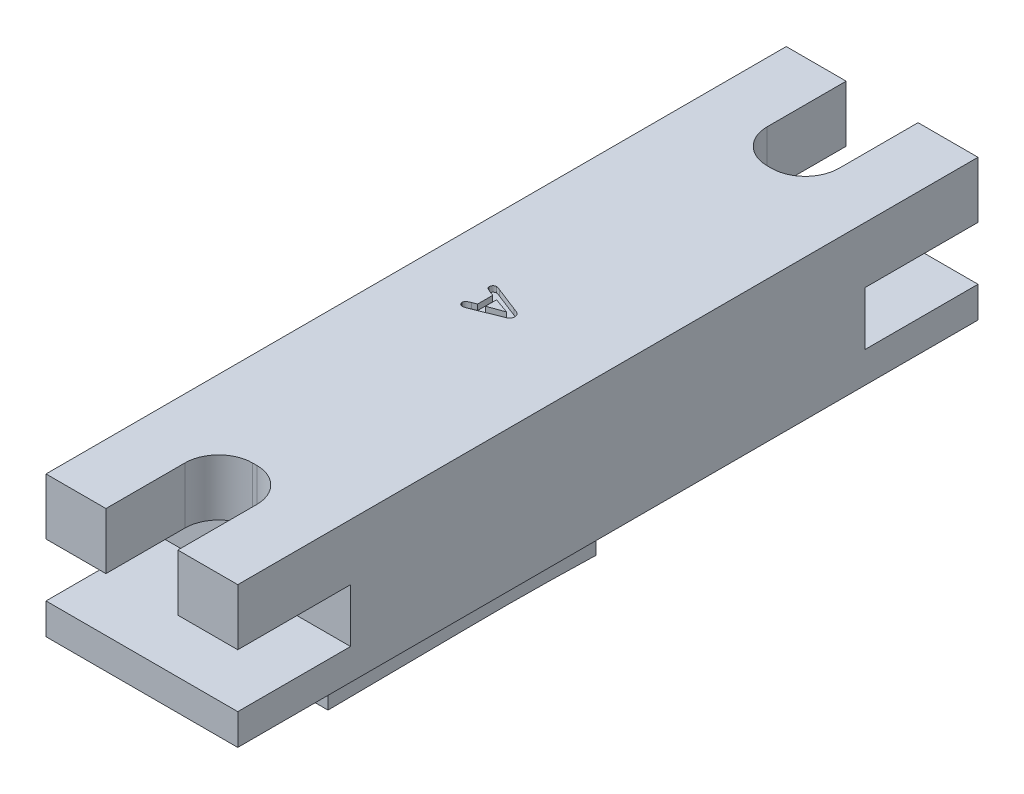
SolidWorks part; units mm, degrees
ref_plane "Front Plane" through (0, 0, 0) normal (0, 0, 1) x (1, 0, 0)
ref_plane "Top Plane" through (0, 0, 0) normal (0, 1, 0) x (1, 0, 0)
ref_plane "Right Plane" through (0, 0, 0) normal (1, 0, 0) x (0, 0, -1)
sketch "Sketch2" plane through (0, 0, 0) normal (0, 1, 0) x (1, 0, 0)
  line L1 (0, 0) -> (17.272, 0)
  line L2 (0, 0) -> (0, 66.675)
  line L3 (0, 66.675) -> (17.272, 66.675)
  line L4 (17.272, 0) -> (17.272, 66.675)
  dimension "D1" = 66.675
  dimension "D2" = 17.272
extrude "Boss-Extrude1" add sketch "Sketch2" along normal blind 12.7
sketch "Sketch3" plane through (0, 0, 0) normal (0, -1, 0) x (1, 0, 0)
  line L0 (17.272, -66.675) -> (0, -66.675) construction
  line L1 (2.54, 0) -> (7.62, 0)
  line L2 (2.54, 0) -> (2.54, -66.675)
  line L3 (2.54, -66.675) -> (7.62, -66.675)
  line L4 (7.62, 0) -> (7.62, -66.675)
  line L5 (0, -66.675) -> (0, 0) construction
  line L6 (0, 0) -> (17.272, 0) construction
  line L7 (-16.0623, -37.465) -> (21.3262, -37.465) construction
  line L8 (-9.1988, -29.21) -> (67.1361, -29.21) construction
  line L9 (2.54, -37.465) -> (2.54, -29.21) construction
  line L10 (-21.0326, -20.955) -> (28.4478, -20.955) construction
  line L11 (5.08, 0) -> (5.08, -66.675) construction
  line L12 (-27.1779, -45.72) -> (27.7068, -45.72) construction
  line L13 (2.54, -48.895) -> (2.54, -50.165)
  line L14 (7.62, -48.895) -> (2.54, -48.895) construction
  line L15 (7.62, -48.895) -> (7.62, -42.545) construction
  line L16 (7.62, -42.545) -> (2.54, -42.545)
  line L17 (2.54, -48.895) -> (2.54, -42.545) construction
  line L18 (7.62, -48.895) -> (2.54, -42.545) construction
  line L19 (7.62, -42.545) -> (2.54, -48.895) construction
  line L20 (7.62, -40.64) -> (2.54, -40.64)
  line L21 (7.62, -40.64) -> (7.62, -34.29)
  line L22 (7.62, -34.29) -> (2.54, -34.29)
  line L23 (2.54, -40.64) -> (2.54, -34.29)
  line L24 (7.62, -40.64) -> (2.54, -34.29) construction
  line L25 (7.62, -34.29) -> (2.54, -40.64) construction
  line L26 (7.62, -32.385) -> (2.54, -32.385)
  line L27 (7.62, -32.385) -> (7.62, -26.035)
  line L28 (7.62, -26.035) -> (2.54, -26.035)
  line L29 (2.54, -32.385) -> (2.54, -26.035)
  line L30 (7.62, -32.385) -> (2.54, -26.035) construction
  line L31 (7.62, -26.035) -> (2.54, -32.385) construction
  line L32 (7.62, -24.13) -> (2.54, -24.13)
  line L33 (7.62, -24.13) -> (7.62, -17.78)
  line L34 (7.62, -17.78) -> (2.54, -17.78)
  line L35 (2.54, -24.13) -> (2.54, -17.78)
  line L36 (7.62, -24.13) -> (2.54, -17.78) construction
  line L37 (7.62, -17.78) -> (2.54, -24.13) construction
  line L38 (2.54, -50.165) -> (7.62, -50.165)
  line L39 (7.62, -50.165) -> (7.62, -48.895)
  line L40 (2.54, -41.91) -> (7.62, -41.91)
  point P16 (2.54, -33.3375)
  point P17 (2.54, -33.3375)
  point P24 (5.08, -45.72)
  point P29 (5.08, -29.21)
  point P30 (5.08, -37.465)
  point P41 (5.08, -20.955)
  dimension "D1" = 5.08
  dimension "D2" = 2.54
  dimension "D3" = 8.255
  dimension "D4" = 8.255
  dimension "D5" = 8.255
  dimension "D6" = 5.08
  dimension "D7" = 6.35
  dimension "D8" = 6.35
  dimension "D9" = 6.35
  dimension "D10" = 6.35
  dimension "D11" = 1.27
  dimension "D12" = 1.27
extrude "Boss-Extrude2" add sketch "Sketch3" along normal blind 12.7 contours L4 L28 L2 L26 | L4 L34 L2 L32 | L4 L32 L2 L28 | L4 L26 L2 L22 | L4 L22 L2 L20 | L2 L40 L4 L20
sketch "Sketch4" plane through (0, 0, 0) normal (0, 0, 1) x (1, 0, 0)
  line L0 (0, 12.7) -> (17.272, 12.7) construction
  line L1 (0, 7.62) -> (5.3975, 7.62)
  line L2 (0, 7.62) -> (0, 2.794)
  line L3 (0, 2.794) -> (17.272, 2.794)
  line L4 (17.272, 7.62) -> (17.272, 2.794)
  line L5 (5.3975, 12.7) -> (11.8745, 12.7)
  line L6 (5.3975, 12.7) -> (5.3975, 7.62)
  line L8 (11.8745, 12.7) -> (11.8745, 7.62)
  line L9 (11.8745, 7.62) -> (17.272, 7.62)
  line L10 (17.272, 12.7) -> (17.272, 0) construction
  line L11 (0, 12.7) -> (0, 0) construction
  point P10 (8.636, 12.7)
  dimension "D2" = 6.477
  dimension "D3" = 4.826
  dimension "D4" = 5.08
extrude "Cut-Extrude1" cut sketch "Sketch4" against normal blind 10.16
ref_plane "Plane1" through (0, 0, -33.3375) normal (0, 0, 1) x (1, 0, 0)
fillet "Fillet2" radius 3.048 2 edges at (11.8745, 10.16, -10.16) (5.3975, 10.16, -10.16)
mirror "Mirror1" about plane through (0, 0, -33.3375) normal (0, 0, 1) of "Fillet2", "Cut-Extrude1"
sketch "Sketch5" plane through (2.54, 0, 0) normal (-1, 0, 0) x (0, 0, 1)
  line L0 (-33.3375, -10.668) -> (-33.3375, -12.7) construction
  line L2 (-66.675, -12.7) -> (0, -12.7)
  line L3 (-66.675, -12.7) -> (-66.675, 0) construction
  line L4 (-17.78, -12.7) -> (-41.91, -12.7) construction
  line L5 (0, -12.7) -> (0, 0) construction
  arc A0 (-66.675, -12.7) -> (0, -12.7) centre (-33.3375, -285.1557) cw
  point P13 (-33.3375, -12.7)
  dimension "D1" = 2.032
  dimension "D2" = 12.7
extrude "Cut-Extrude4" cut sketch "Sketch5" against normal through all
fillet "Fillet1" [suppressed] radius 2.54
sketch "Sketch6" plane through (0, 12.7, 0) normal (0, 1, 0) x (1, 0, 0)
  line L0 (5.3975, 7.112) -> (5.3975, 59.563) construction
  arc A0 (8.4455, 10.16) -> (5.3975, 7.112) centre (8.4455, 7.112) ccw construction
  text T0 "A\r\n" font "Arial Rounded MT Bold" height 3.5
extrude "Cut-Extrude5" cut sketch "Sketch6" against normal blind 0.508
sketch "Sketch7" plane through (2.54, 0, 0) normal (-1, 0, 0) x (0, 0, 1)
  line L0 (-66.675, 0) -> (0, 0)
  line L1 (-33.3375, 0) -> (-33.3375, -10.668) construction
  line L2 (-31.3055, -10.6755) -> (-10.16, -10.8785)
  line L3 (-41.91, 0) -> (-41.91, -10.8019)
  line L4 (-17.78, -11.1092) -> (-17.78, 0)
  line L5 (-17.78, 0) -> (-41.91, 0)
  line L7 (-17.78, -11.1092) -> (-17.78, 0)
  line L8 (-17.78, 0) -> (-41.91, 0)
  line L12 (-41.91, 0) -> (-41.91, -10.8019)
  arc A0 (-17.78, -11.1092) -> (-41.91, -10.8019) centre (-33.3375, -285.1557) ccw construction
  arc A1 (-17.78, -11.1092) -> (-41.91, -10.8019) centre (-33.3375, -285.1557) ccw
  arc A2 (-17.78, -11.1092) -> (-41.91, -10.8019) centre (-33.3375, -285.1557) ccw
  arc M10 (-41.91, -10.8019) -> (-17.78, -11.1092) centre (-33.3375, -285.1557) cw
  line M11 (-17.78, -11.1092) -> (-17.78, 0)
  dimension "D2" = 0.55
  dimension "D3" = 2.032
  dimension "D1" = 0
extrude "Cut-Extrude6" cut sketch "Sketch7" against normal through all contours L2 M10 M11
